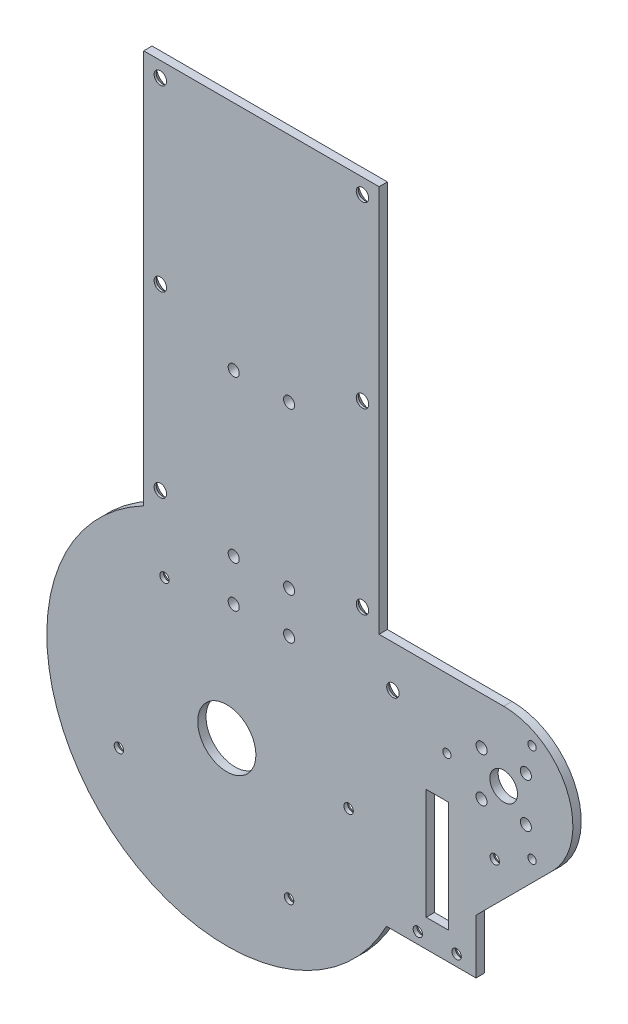
SolidWorks part; units mm, degrees
ref_plane "前视基准面" through (0, 0, 0) normal (0, 0, 1) x (1, 0, 0)
ref_plane "上视基准面" through (0, 0, 0) normal (0, 1, 0) x (1, 0, 0)
ref_plane "右视基准面" through (0, 0, 0) normal (1, 0, 0) x (0, 0, -1)
sketch "Sketch1" plane through (0, 0, 0) normal (0, 0, 1) x (1, 0, 0)
  line L0 (-10.9179, 60) -> (113.3582, 60) construction
  line L3 (-33.1662, 50) -> (-60, 50)
  line L4 (-60, 0) -> (-60, 50)
  line L6 (56.8821, -30) -> (90, -30)
  line L7 (90, -10.3553) -> (117.6777, 17.3223)
  line L13 (0, 60) -> (100, 60)
  line L14 (76, 5.7859) -> (76, -20.6668) construction
  line L16 (72, 20) -> (80, 20)
  line L17 (72, 20) -> (72, -20)
  line L18 (72, -20) -> (80, -20)
  line L19 (80, 20) -> (80, -20)
  line L20 (72, 20) -> (80, -20) construction
  line L21 (72, -20) -> (80, 20) construction
  line L25 (90, -30) -> (90, -10.3553)
  line L26 (56.8821, -30) -> (51.9615, -30)
  line L27 (57.5629, -26) -> (85.1685, -26) construction
  arc A0 (0, 60) -> (51.9615, -30) centre (0, 0) ccw
  circle A2 centre (0, 0) radius 10.5
  arc A8 (117.6777, 17.3223) -> (100, 60) centre (100, 35) ccw
  circle A9 centre (100, 35) radius 5
  point P21 (76, 0)
  point P31 (83, -26)
  point P32 (69, -26)
  dimension "D1" = 120
  dimension "D2" = 90
  dimension "D3" = 21
  dimension "D5" = 50
  dimension "D4" = 100
  dimension "D6" = 10
  dimension "D7" = 10
  dimension "D8" = 8
  dimension "D9" = 40
  dimension "D10" = 150
  dimension "D11" = 6
extrude "Boss-Extrude1" add sketch "Sketch1" along normal blind 3
sketch "Sketch2" plane through (0, 0, 3) normal (0, 0, 1) x (1, 0, 0)
  line L1 (-60, 0) -> (-60, 50) construction
  line L2 (0, 60) -> (100, 60) construction
  circle A1 centre (0, 0) radius 57
  circle A2 centre (60, 45) radius 2
  circle A6 centre (100, 35) radius 14
  point P9 (60, 45)
  dimension "D1" = 15
  dimension "D5" = 28
  dimension "D2" = 120
extrude "Cut-Extrude1" cut sketch "Sketch2" against normal up to next
sketch "Sketch3" plane through (0, 0, 0) normal (0, 0, -1) x (-1, 0, 0)
  line L4 (-30, 0) -> (-30, 80)
  line L5 (-30, 80) -> (5, 80)
  line L6 (5, 80) -> (5, 48)
  line L7 (5, 48) -> (25.3049, 16.1141)
  circle A2 centre (0, 0) radius 10.5
  arc A4 (-30, 0) -> (25.3049, 16.1141) centre (0, 0) ccw
  dimension "D1" = 80
  dimension "D2" = 35
  dimension "D3" = 32
extrude "Boss-Extrude2" add sketch "Sketch3" against normal blind 3
sketch "Sketch4" plane through (0, 0, 0) normal (0, 0, -1) x (-1, 0, 0)
  line L0 (-30, 80) -> (5, 80) construction
  line L1 (5, 80) -> (5, 48) construction
  line L3 (-20, 65.5961) -> (-5, 65.5961)
  line L4 (-20, 65.5961) -> (-20, 63.5961)
  line L5 (-20, 63.5961) -> (-5, 63.5961)
  line L6 (-5, 65.5961) -> (-5, 63.5961)
  line L7 (-20, 65.5961) -> (-5, 63.5961) construction
  line L8 (-20, 63.5961) -> (-5, 65.5961) construction
  line L9 (-13.5, 72.0961) -> (-11.5, 72.0961)
  line L10 (-13.5, 72.0961) -> (-13.5, 57.0961)
  line L11 (-13.5, 57.0961) -> (-11.5, 57.0961)
  line L12 (-11.5, 72.0961) -> (-11.5, 57.0961)
  line L13 (-13.5, 72.0961) -> (-11.5, 57.0961) construction
  line L14 (-13.5, 57.0961) -> (-11.5, 72.0961) construction
  point P5 (-12.5, 64.5961)
  point P10 (-12.5, 80)
  point P11 (-12.5, 64.5961)
  dimension "D1" = 15
  dimension "D2" = 2
  dimension "D3" = 0
  dimension "D4" = 15
  dimension "D5" = 2
sketch "Sketch5" plane through (0, 0, 3) normal (0, 0, 1) x (1, 0, 0)
  line L0 (100, 48.4826) -> (100, 24.1919) construction
  line L1 (89.5844, 35) -> (110.5191, 35) construction
  circle A0 centre (92, 43) radius 2
  circle A1 centre (108, 43) radius 2
  circle A2 centre (108, 27) radius 2
  circle A3 centre (92, 27) radius 2
  dimension "D1" = 8
  dimension "D2" = 8
extrude "Cut-Extrude2" cut sketch "Sketch5" against normal blind 10
sketch "Sketch6" plane through (0, 0, 3) normal (0, 0, 1) x (1, 0, 0)
  line L0 (12.5, 60) -> (12.5, 200) construction
  line L1 (30, 80) -> (-5, 80) construction
  line L2 (12.5, 60) -> (55, 60)
  line L3 (-30, 60) -> (-30, 200)
  line L4 (-30, 200) -> (55, 200)
  line L5 (55, 60) -> (55, 200)
  line L6 (-30, 60) -> (55, 200) construction
  line L7 (-30, 200) -> (55, 60) construction
  line L8 (-30, 60) -> (-30, 51.9615)
  line L9 (12.5, 60) -> (-5, 60)
  line L10 (-5, 80) -> (-5, 59.7913) construction
  line L11 (-5, 60) -> (-5, 59.7913)
  arc A0 (-5, 59.7913) -> (-33.1662, 50) centre (0, 0) ccw construction
  arc A1 (-5, 59.7913) -> (-30, 51.9615) centre (0, 0) ccw
  point P2 (12.5, 130)
  point P10 (12.5, 80)
  dimension "D1" = 85
extrude "Boss-Extrude4" add sketch "Sketch6" against normal up to surface (3 mm away) up to face at (94, 27, 0)
sketch "Sketch7" plane through (0, 0, 3) normal (0, 0, 1) x (1, 0, 0)
  line L0 (55, 130) -> (-30, 130) construction
  line L1 (55, 60) -> (55, 200) construction
  line L2 (-30, 200) -> (-30, 51.9615) construction
  line L3 (12.5, 200) -> (12.5, 60) construction
  line L4 (55, 200) -> (-30, 200) construction
  circle A0 centre (-24, 194.5) radius 2
  circle A1 centre (49, 194.5) radius 2
  circle A2 centre (49, 65.5) radius 2
  circle A3 centre (-24, 65.5) radius 2
  circle A4 centre (-24, 130) radius 2
  circle A5 centre (49, 130) radius 2
  dimension "D1" = 4
  dimension "D2" = 4
  dimension "D3" = 6
  dimension "D4" = 5.5
  dimension "D5" = 5.5
  dimension "D6" = 6
sketch "Sketch8" plane through (0, 0, 3) normal (0, 0, 1) x (1, 0, 0)
  circle A0 centre (0, 0) radius 65
  circle A1 centre (0, 0) radius 10.5
extrude "Boss-Extrude5" add sketch "Sketch8" against normal up to surface (3 mm away) up to face at (29.1005, 48.492, 0)
sketch "Sketch9" plane through (0, 0, 3) normal (0, 0, 1) x (1, 0, 0)
  line L0 (-60, 50) -> (-60, 25)
  line L1 (-60, 50) -> (-41.5331, 50)
  arc A0 (-41.5331, 50) -> (-60, 25) centre (0, 0) ccw
extrude "Cut-Extrude4" cut sketch "Sketch9" against normal blind 10
sketch "Sketch10" plane through (0, 0, 3) normal (0, 0, 1) x (1, 0, 0)
  circle A0 centre (-22.5, 38.9711) radius 1.5
  circle A1 centre (-38.9711, -22.5) radius 1.5
  circle A2 centre (22.5, -38.9711) radius 1.5
  circle A3 centre (96.7678, 10.5546) radius 1.5
sketch "Sketch11" plane through (0, 0, 0) normal (0, 0, -1) x (-1, 0, 0)
  circle A0 centre (-2.5, 116.34) radius 2
  circle A5 centre (-22.5, 116.34) radius 2
  dimension "D1" = 116.34
extrude "Cut-Extrude6" cut sketch "Sketch11" against normal up to next
sketch "Sketch12" plane through (0, 0, 0) normal (0, 0, -1) x (-1, 0, 0)
  circle A0 centre (-2.5, 58.1605) radius 2
  circle A1 centre (-22.5, 58.1605) radius 2
  circle A2 centre (-2.5, 43.1605) radius 2
  circle A3 centre (-22.5, 43.1605) radius 2
extrude "Cut-Extrude7" cut sketch "Sketch12" against normal up to next
sketch "Sketch13" plane through (0, 0, 0) normal (0, 0, -1) x (-1, 0, 0)
  point P0 (-22.5, -38.9711)
  point P1 (38.9711, -22.5)
  point P3 (-96.7678, 10.5546)
  point P5 (22.5, 38.9711)
hole_wizard "CSK for M3 SFHCS1" positions "Sketch14" profile "Sketch15" countersink size "M3" standard "ANSI Metric"
sketch "Sketch14" plane through (0, 0, 0) normal (0, 0, -1) x (-1, 0, 0)
  point P0 (22.5, 38.9711)
  point P3 (38.9711, -22.5)
  point P6 (-22.5, -38.9711)
  point P9 (-96.7678, 10.5546)
sketch "Sketch15" plane through (-22.5, 38.9711, 0) normal (1, 0, 0) x (0, 1, 0)
  line L0 (0, 0) -> (0, 12.3215)
  line L1 (0, 12.3215) -> (1.7, 11.3)
  line L2 (1.7, 11.3) -> (1.7, 1.66)
  line L3 (1.7, 1.66) -> (3.36, 0)
  line L5 (3.36, 0) -> (0, 0)
  line L6 (-1.7, 1.66) -> (-3.36, 0) construction
  line L10 (0, 12.3215) -> (-1.7, 11.3) construction
  line L11 (0, -6.35) -> (0, 107.95) construction
  dimension "Hole Dia." = 3.4
  dimension "Hole Depth" = 11.3
  dimension "Near C'Sink Dia." = 6.72
  dimension "Near C'Sink Angle" = 90
  dimension "Drill Angle" = 118
sketch "Sketch16" plane through (0, 0, 0) normal (0, 0, -1) x (-1, 0, 0)
  point P0 (-49, 194.5)
  point P1 (24, 194.5)
  point P3 (24, 130)
  point P5 (-49, 130)
  point P7 (-49, 65.5)
  point P9 (24, 65.5)
hole_wizard "CSK for M4 SFHCS1" positions "Sketch17" profile "Sketch18" countersink size "M4" standard "ANSI Metric"
sketch "Sketch17" plane through (0, 0, 0) normal (0, 0, -1) x (-1, 0, 0)
  point P0 (-49, 194.5)
  point P3 (24, 194.5)
  point P6 (24, 130)
  point P9 (-49, 130)
  point P12 (-49, 65.5)
  point P15 (24, 65.5)
sketch "Sketch18" plane through (49, 194.5, 0) normal (1, 0, 0) x (0, 1, 0)
  line L0 (0, 0) -> (0, 12.6519)
  line L1 (0, 12.6519) -> (2.25, 11.3)
  line L2 (2.25, 11.3) -> (2.25, 2.23)
  line L3 (2.25, 2.23) -> (4.48, 0)
  line L5 (4.48, 0) -> (0, 0)
  line L6 (-2.25, 2.23) -> (-4.48, 0) construction
  line L10 (0, 12.6519) -> (-2.25, 11.3) construction
  line L11 (0, -6.35) -> (0, 107.95) construction
  dimension "Hole Dia." = 4.5
  dimension "Hole Depth" = 11.3
  dimension "Near C'Sink Dia." = 8.96
  dimension "Near C'Sink Angle" = 90
  dimension "Drill Angle" = 118
hole_wizard "CSK for M3 SFHCS2" positions "Sketch19" profile "Sketch20" countersink size "M3" standard "ANSI Metric"
sketch "Sketch19" plane through (0, 0, 0) normal (0, 0, -1) x (-1, 0, 0)
  point P0 (-83, -26)
  point P3 (-69, -26)
sketch "Sketch20" plane through (83, -26, 0) normal (1, 0, 0) x (0, 1, 0)
  line L0 (0, 0) -> (0, 12.3215)
  line L1 (0, 12.3215) -> (1.7, 11.3)
  line L2 (1.7, 11.3) -> (1.7, 1.66)
  line L3 (1.7, 1.66) -> (3.36, 0)
  line L5 (3.36, 0) -> (0, 0)
  line L6 (-1.7, 1.66) -> (-3.36, 0) construction
  line L10 (0, 12.3215) -> (-1.7, 11.3) construction
  line L11 (0, -6.35) -> (0, 107.95) construction
  dimension "Hole Dia." = 3.4
  dimension "Hole Depth" = 11.3
  dimension "Near C'Sink Dia." = 6.72
  dimension "Near C'Sink Angle" = 90
  dimension "Drill Angle" = 118
hole_wizard "CSK for M4 SFHCS2" positions "Sketch21" profile "Sketch22" countersink size "M4" standard "ANSI Metric"
sketch "Sketch21" plane through (0, 0, 0) normal (0, 0, -1) x (-1, 0, 0)
  point P0 (-60, 45)
sketch "Sketch22" plane through (60, 45, 0) normal (1, 0, 0) x (0, 1, 0)
  line L0 (0, 0) -> (0, 12.6519)
  line L1 (0, 12.6519) -> (2.25, 11.3)
  line L2 (2.25, 11.3) -> (2.25, 2.23)
  line L3 (2.25, 2.23) -> (4.48, 0)
  line L5 (4.48, 0) -> (0, 0)
  line L6 (-2.25, 2.23) -> (-4.48, 0) construction
  line L10 (0, 12.6519) -> (-2.25, 11.3) construction
  line L11 (0, -6.35) -> (0, 107.95) construction
  dimension "Hole Dia." = 4.5
  dimension "Hole Depth" = 11.3
  dimension "Near C'Sink Dia." = 8.96
  dimension "Near C'Sink Angle" = 90
  dimension "Drill Angle" = 118
sketch "Sketch23" plane through (0, 0, 0) normal (0, 0, -1) x (-1, 0, 0)
  line L0 (-82, 35) -> (-75, 35) construction
  line L1 (-109, 19.4115) -> (-112.5, 13.3494) construction
  line L3 (-109, 50.5885) -> (-112.5, 56.6506) construction
  circle A5 centre (-100, 35) radius 20.5 construction
  circle A6 centre (-79.5, 35) radius 1.5
  circle A7 centre (-110.25, 17.2465) radius 1.5
  circle A8 centre (-110.25, 52.7535) radius 1.5
  point P6 (-110.75, 53.6195)
  point P7 (-110.75, 16.3805)
  point P8 (-73.5, 35)
  point P19 (-110.75, 53.6195)
  dimension "D1" = 3
  dimension "D2" = 3
extrude "Cut-Extrude8" cut sketch "Sketch23" against normal up to next
sketch "Sketch24" plane through (0, 0, 3) normal (0, 0, 1) x (1, 0, 0)
  point P4 (44, 0)
hole_wizard "CSK for M3 SFHCS3" positions "Sketch27" profile "Sketch28" countersink size "M3" standard "ANSI Metric"
sketch "Sketch27" plane through (0, 0, 0) normal (0, 0, -1) x (-1, 0, 0)
  point P0 (-44, 0)
sketch "Sketch28" plane through (44, 0, 0) normal (1, 0, 0) x (0, 1, 0)
  line L0 (0, 0) -> (0, 12.3215)
  line L1 (0, 12.3215) -> (1.7, 11.3)
  line L2 (1.7, 11.3) -> (1.7, 1.66)
  line L3 (1.7, 1.66) -> (3.36, 0)
  line L5 (3.36, 0) -> (0, 0)
  line L6 (-1.7, 1.66) -> (-3.36, 0) construction
  line L10 (0, 12.3215) -> (-1.7, 11.3) construction
  line L11 (0, -6.35) -> (0, 107.95) construction
  dimension "Hole Dia." = 3.4
  dimension "Hole Depth" = 11.3
  dimension "Near C'Sink Dia." = 6.72
  dimension "Near C'Sink Angle" = 90
  dimension "Drill Angle" = 118
